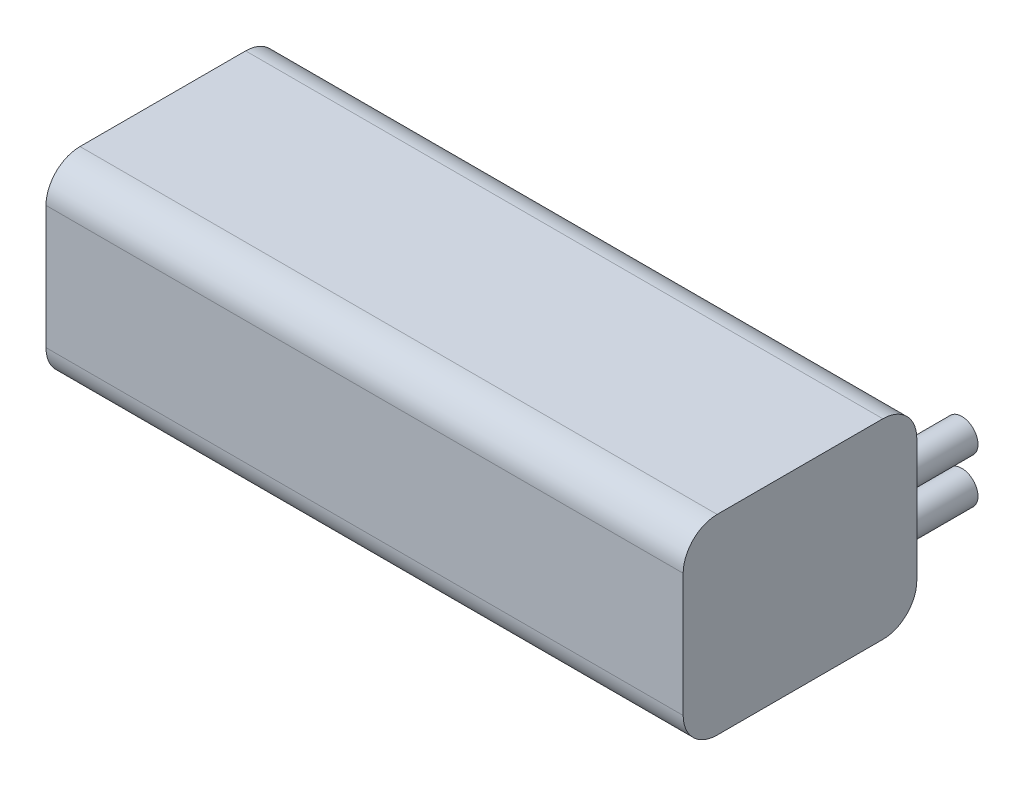
SolidWorks part; units mm, degrees
ref_plane "Plano frontal" through (0, 0, 0) normal (0, 0, 1) x (1, 0, 0)
ref_plane "Plano superior" through (0, 0, 0) normal (0, 1, 0) x (1, 0, 0)
ref_plane "Plano direito" through (0, 0, 0) normal (1, 0, 0) x (0, 0, -1)
sketch "Esboço1" plane through (0, 0, 0) normal (0, 1, 0) x (1, 0, 0)
  line L1 (75, -27.5) -> (-75, -27.5)
  line L2 (75, -27.5) -> (75, 27.5)
  line L3 (75, 27.5) -> (-75, 27.5)
  line L4 (-75, -27.5) -> (-75, 27.5)
  line L5 (75, -27.5) -> (-75, 27.5) construction
  line L6 (75, 27.5) -> (-75, -27.5) construction
  point P0 (0, 0)
  dimension "D1" = 150
  dimension "D2" = 55
extrude "Ressalto-extrusão1" add sketch "Esboço1" along normal blind 45
fillet "Filete1" radius 8 4 edges at (0, 0, -27.5) (0, 0, 27.5) (0, 45, 27.5) (0, 45, -27.5)
sketch "Esboço2" plane through (0, 0, -27.5) normal (0, 0, -1) x (-1, 0, 0)
  circle A0 centre (-68.7919, 15.5817) radius 3.81
extrude "Ressalto-extrusão2" add sketch "Esboço2" along normal blind 16.806
sketch "Esboço4" plane through (0, 0, -27.5) normal (0, 0, -1) x (-1, 0, 0)
  circle A0 centre (-68.7919, 26.1649) radius 3.81
extrude "Ressalto-extrusão3" add sketch "Esboço4" along normal blind 16.806
